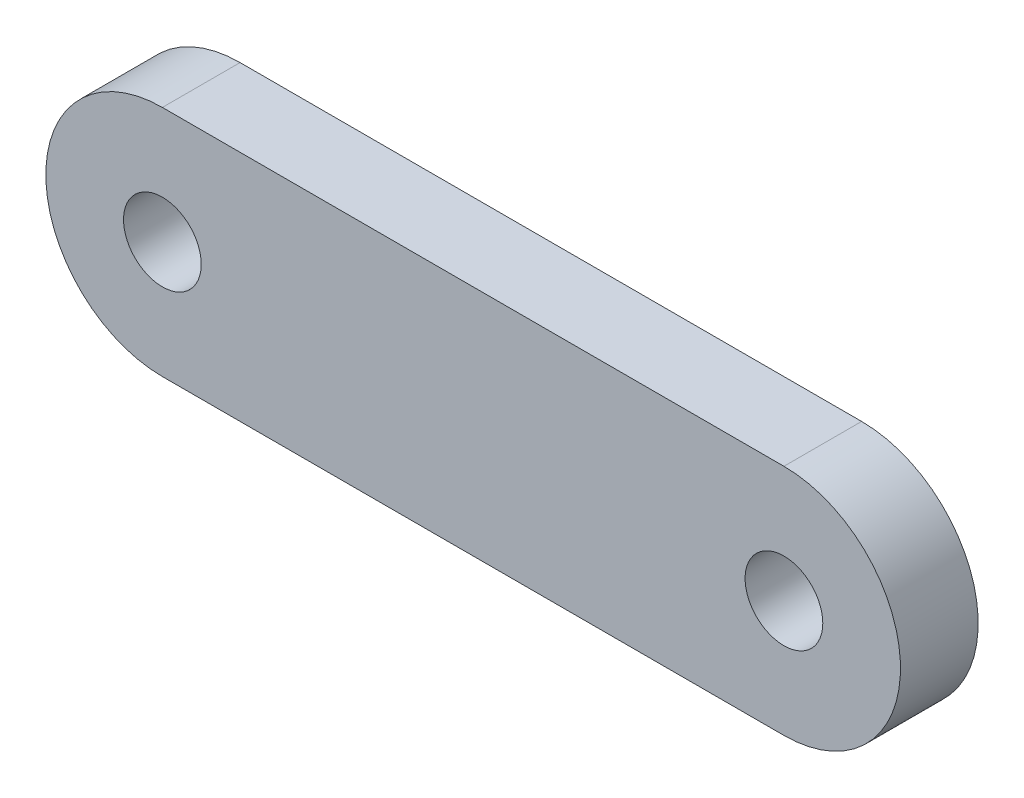
SolidWorks part; units mm, degrees
ref_plane "Front Plane" through (0, 0, 0) normal (0, 0, 1) x (1, 0, 0)
ref_plane "Top Plane" through (0, 0, 0) normal (0, 1, 0) x (1, 0, 0)
ref_plane "Right Plane" through (0, 0, 0) normal (1, 0, 0) x (0, 0, -1)
sketch "Sketch2" plane through (0, 0, 0) normal (0, 0, 1) x (1, 0, 0)
  line L0 (-5.1635, 0) -> (2.8365, 0) construction
  line L1 (-5.1635, 1.5) -> (2.8365, 1.5)
  line L2 (-5.1635, -1.5) -> (2.8365, -1.5)
  arc A0 (-5.1635, 1.5) -> (-5.1635, -1.5) centre (-5.1635, 0) ccw
  arc A1 (2.8365, -1.5) -> (2.8365, 1.5) centre (2.8365, 0) ccw
  circle A2 centre (2.8365, 0) radius 0.5
  circle A3 centre (-5.1635, 0) radius 0.5
  point P3 (-1.1635, 0)
  dimension "D2" = 1
  dimension "D3" = 1
  dimension "D4" = 1.5
  dimension "D1" = 8
extrude "Boss-Extrude1" add sketch "Sketch2" along normal blind 1
